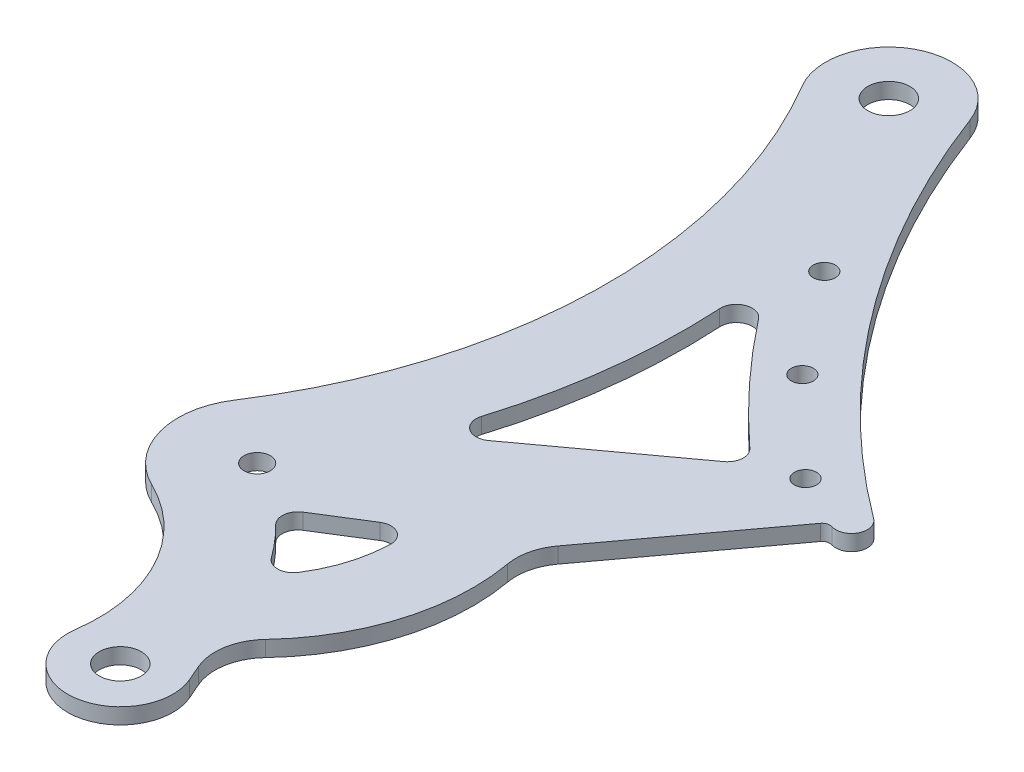
SolidWorks part; units mm, degrees
ref_plane "前视基准面" through (0, 0, 0) normal (0, 0, 1) x (1, 0, 0)
ref_plane "上视基准面" through (0, 0, 0) normal (0, 1, 0) x (1, 0, 0)
ref_plane "右视基准面" through (0, 0, 0) normal (1, 0, 0) x (0, 0, -1)
sketch "Sketch1" plane through (0, 0, 0) normal (0, 1, 0) x (1, 0, 0)
  line L0 (0, 0) -> (-20, 46) construction
  line L1 (-20, 46) -> (27.5874, 110.3074) construction
  line L2 (27.5874, 110.3074) -> (47.6835, 95.4363) construction
  line L5 (9.1707, 3.9873) -> (7.8769, 6.9631)
  line L6 (43.3752, 89.6143) -> (22.1614, 60.947)
  circle A0 centre (0, 0) radius 4
  circle A1 centre (-20, 46) radius 2.5
  arc A2 (-9.9049, 1.3756) -> (9.1707, 3.9873) centre (0, 0) ccw
  arc A3 (9.7833, 17.8228) -> (20.3567, 53.2342) centre (-20, 46) ccw
  arc A4 (-32.5627, 54.1962) -> (-26.5399, 32.5008) centre (-20, 46) ccw
  arc A5 (-9.9049, 1.3756) -> (-26.5399, 32.5008) centre (-39.6198, 5.5023) ccw
  arc A6 (22.1614, 60.947) -> (20.3567, 53.2342) centre (30.1999, 54.9986) ccw
  arc A7 (7.8769, 6.9631) -> (9.7833, 17.8228) centre (17.0476, 10.9503) cw
  arc A8 (-8.7669, 170.2212) -> (-30.3194, 159.8754) centre (-20, 166) ccw
  arc A9 (-32.5627, 54.1962) -> (-30.3194, 159.8754) centre (-116.3143, 108.8375) ccw
  arc A10 (-8.7669, 170.2212) -> (47.6835, 95.4363) centre (146.0849, 228.4112) ccw
  arc A11 (45.0203, 90.1563) -> (47.6835, 95.4363) centre (45.899, 93.0248) ccw
  arc A12 (45.0203, 90.1563) -> (43.3752, 89.6143) centre (44.581, 88.7221) ccw
  dimension "D3" = 8
  dimension "D4" = 5
  dimension "D5" = 20
  dimension "D7" = 15
  dimension "D8" = 25
  dimension "D10" = 82
  dimension "D11" = 60
  dimension "D12" = 10
  dimension "D13" = 24
  dimension "D14" = 200
  dimension "D16" = 6
  dimension "D17" = 1.5
  dimension "D1" = 20
  dimension "D2" = 46
  dimension "D6" = 120
  dimension "D9" = 80
  dimension "D15" = 120
extrude "Boss-Extrude2" add sketch "Sketch1" along normal blind 3
sketch "Sketch2" plane through (0, 3, 0) normal (0, 1, 0) x (1, 0, 0)
  line L5 (24.0865, 90.6178) -> (-1.7618, 71.7124)
  line L6 (10.1038, 69.8697) -> (27.0748, 92.8034)
  line L8 (1.3999, 47.9612) -> (-7.6072, 42.3183)
  arc A0 (-3.0985, 31.793) -> (1.8583, 31.9212) centre (-0.6638, 33.5457) ccw
  arc A1 (-8.1148, 37.6339) -> (-7.6072, 42.3183) centre (-6.0145, 39.776) cw
  arc A2 (1.3999, 47.9612) -> (5.9917, 45.3431) centre (2.9927, 45.4189) cw
  arc A3 (24.0865, 90.6178) -> (24.3398, 95.2533) centre (22.3155, 93.0392) ccw
  arc A4 (-1.7618, 71.7124) -> (-6.4002, 75.0162) centre (-3.5329, 74.1339) cw
  arc A5 (3.8596, 117.3939) -> (-1.5004, 115.3773) centre (1.4947, 115.5479) ccw
  circle A6 centre (-20, 166) radius 4
  arc A22 (10.1038, 69.8697) -> (5.5921, 50.5875) centre (30.1999, 54.9986) ccw
  arc A23 (-2.6433, 126.27) -> (27.0748, 92.8034) centre (146.0849, 228.4112) ccw
  arc A24 (-20, 46) -> (-2.6433, 126.27) centre (-116.3143, 108.8375) ccw
  arc A25 (-0.8738, 28.3879) -> (-20, 46) centre (-39.6198, 5.5023) ccw
  arc A26 (-0.8738, 28.3879) -> (5.5921, 50.5875) centre (-20, 46) ccw
  arc A28 (3.8596, 117.3939) -> (24.3398, 95.2533) centre (146.0849, 228.4112) ccw
  arc A29 (-6.4002, 75.0162) -> (-1.5004, 115.3773) centre (-116.3143, 108.8375) ccw
  arc A30 (-3.0985, 31.793) -> (-8.1148, 37.6339) centre (-39.6198, 5.5023) ccw
  arc A31 (1.8583, 31.9212) -> (5.9917, 45.3431) centre (-20, 46) ccw
  dimension "D2" = 3
  dimension "D3" = 8
  dimension "D1" = 15
extrude "Cut-Extrude2" cut sketch "Sketch2" against normal up to next
sketch "Sketch3" plane through (0, 3, 0) normal (0, 1, 0) x (1, 0, 0)
  line L0 (2.3097, 131.4336) -> (146.0849, 228.4112) construction
  line L1 (146.0849, 228.4112) -> (17.2056, 112.3678) construction
  line L2 (146.0849, 228.4112) -> (34.61, 95.5606) construction
  line L3 (146.0849, 228.4112) -> (146.0849, 54.987) construction
  circle A0 centre (146.0849, 228.4112) radius 173.4243 construction
  circle A1 centre (2.3097, 131.4336) radius 2.1
  circle A2 centre (34.61, 95.5606) radius 2.1
  circle A3 centre (17.2056, 112.3678) radius 2.1
  circle A4 centre (-20, 166) radius 4 construction
  dimension "D1" = 4.2
  dimension "D2" = 8
  dimension "D3" = 8
  dimension "D4" = 40
extrude "Cut-Extrude3" cut sketch "Sketch3" against normal up to next
